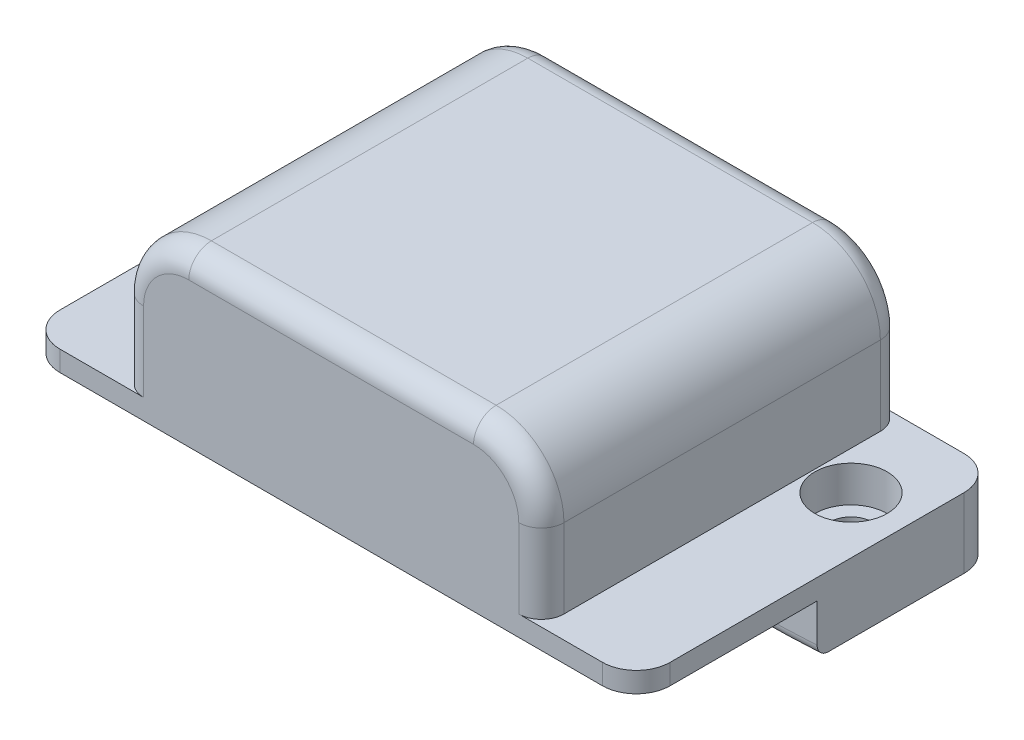
SolidWorks part; units mm, degrees
ref_plane "前视基准面" through (0, 0, 0) normal (0, 0, 1) x (1, 0, 0)
ref_plane "上视基准面" through (0, 0, 0) normal (0, 1, 0) x (1, 0, 0)
ref_plane "右视基准面" through (0, 0, 0) normal (1, 0, 0) x (0, 0, -1)
other "Configuration Table"
sketch "草图1" plane through (0, 0, 0) normal (0, 0, 1) x (1, 0, 0)
  line L0 (0, 65.0084) -> (0, -40.235) construction
  line L1 (-11, -3.0444) -> (-11, 5.3912) construction
  line L3 (55, 0) -> (-55, 0) construction
  line L8 (-13.5, 0) -> (-13.5, 3.5)
  line L9 (-13.5, 3.5) -> (-9.3, 3.5)
  line L10 (-9.3, 3.5) -> (-9.3, 10)
  line L11 (-9.3, 10) -> (9.3, 10)
  line L12 (9.3, 10) -> (9.3, 3.5)
  line L13 (9.3, 3.5) -> (13.5, 3.5)
  line L14 (13.5, 3.5) -> (13.5, 0)
  line L15 (-11, -3.0444) -> (11, -3.0444) construction
  line L16 (11, -3.0444) -> (11, 5.3912) construction
  line L17 (-13.5, 0) -> (13.5, 0)
  dimension "D1" = 10
  dimension "D2" = 27
  dimension "D3" = 18.6
  dimension "D4" = 3.5
  dimension "D5" = 22
extrude "凸台-拉伸1" add sketch "草图1" along normal mid plane 8
sketch "草图2" plane through (0, 0, 0) normal (0, -1, 0) x (1, 0, 0)
  line L0 (-15.998, 0) -> (16.2146, 0) construction
  line L2 (0, 10.6142) -> (0, -10.7139) construction
  circle A0 centre (-11, 0) radius 0.95
  circle A1 centre (11, 0) radius 0.95
  dimension "D2" = 1.9
  dimension "D1" = 22
extrude "切除-拉伸1" cut sketch "草图2" against normal up to next
sketch "草图3" plane through (0, 3.5, 0) normal (0, 1, 0) x (1, 0, 0)
  circle A0 centre (-11, 0) radius 1.5
  dimension "D1" = 3
sketch "草图5" plane through (0, 0, 0) normal (0, -1, 0) x (-1, 0, 0)
  line L0 (13.5, -4) -> (-13.5, -4) construction
  line L1 (7.8, -4) -> (-7.8, -4)
  line L2 (7.8, -4) -> (7.8, 2)
  line L3 (7.8, 2) -> (-7.8, 2)
  line L4 (-7.8, -4) -> (-7.8, 2)
  line L5 (0, -7.5091) -> (0, 7.4286) construction
  line L7 (9.3, -4) -> (9.3, 4) construction
  line L8 (13.5, 4) -> (-13.5, 4) construction
  dimension "D1" = 1.5
  dimension "D2" = 2
extrude "切除-拉伸2" cut sketch "草图5" against normal offset from surface (8.5 mm away) 1.5 up to face at (0, 10, 0)
sketch "草图8" plane through (0, 0, -4) normal (0, 0, -1) x (-1, 0, 0)
  line L0 (-18.4937, 0.9601) -> (-18.4937, -4.0399)
  line L1 (-18.4937, -4.0399) -> (18.4937, -4.0399)
  line L2 (18.4937, 0.9601) -> (18.4937, -4.0399)
  arc A0 (-18.4937, 0.9601) -> (-3.9261, 0.742) centre (-10.4695, 50.312) ccw construction
  arc A1 (3.9261, 0.742) -> (-3.9261, 0.742) centre (0, -29) ccw construction
  arc A2 (3.9261, 0.742) -> (18.4937, 0.9601) centre (10.4695, 50.312) ccw construction
  arc A3 (-18.4937, 0.9601) -> (-3.9261, 0.742) centre (-10.4695, 50.312) ccw
  arc A4 (3.9261, 0.742) -> (-3.9261, 0.742) centre (0, -29) ccw
  arc A5 (3.9261, 0.742) -> (18.4937, 0.9601) centre (10.4695, 50.312) ccw
  dimension "D1" = 5
extrude "切除-拉伸4" cut sketch "草图8" against normal through all
sketch "草图11" plane through (0, 0, 4) normal (0, 0, 1) x (1, 0, 0)
  line L0 (13.5, 2.6) -> (7.8, 2.6)
  line L1 (-7.8, 2.6) -> (-13.5, 2.6)
  line L7 (7.8, 8.5) -> (7.8, 0.3833)
  line L15 (-9.3, 10) -> (-9.3, 3.5)
  line L16 (-9.3, 3.5) -> (-13.5, 3.5)
  line L17 (-13.5, 3.5) -> (-13.5, 0.4039)
  line L18 (-7.8, 0.3833) -> (-7.8, 8.5)
  line L25 (-9.3, 10) -> (-9.3, 3.5)
  line L26 (-9.3, 3.5) -> (-13.5, 3.5)
  line L27 (-13.5, 3.5) -> (-13.5, 2.6)
  line L28 (-7.8, 2.6) -> (-7.8, 8.5)
  line L30 (7.8, 8.5) -> (7.8, 2.6)
  line L31 (13.5, 0.4039) -> (13.5, 3.5)
  line L32 (13.5, 2.6) -> (13.5, 3.5)
  line L33 (13.5, 3.5) -> (9.3, 3.5)
  line L34 (13.5, 3.5) -> (9.3, 3.5)
  line L35 (9.3, 3.5) -> (9.3, 10)
  line L36 (9.3, 3.5) -> (9.3, 10)
  line L37 (9.3, 10) -> (-9.3, 10)
  line L38 (9.3, 10) -> (-9.3, 10)
  line L39 (-7.8, 8.5) -> (7.8, 8.5)
  line L40 (-7.8, 8.5) -> (7.8, 8.5)
  arc A2 (7.8, 0.3833) -> (13.5, 0.4039) centre (10.4695, 50.312) ccw
  arc A3 (-13.5, 0.4039) -> (-7.8, 0.3833) centre (-10.4695, 50.312) ccw
  dimension "D2" = 0.9
  dimension "D1" = 0
extrude "凸台-拉伸2" add sketch "草图11" along normal blind 8
sketch "草图12" plane through (0, 8.5, 0) normal (0, -1, 0) x (1, 0, 0)
  line L0 (7.8, -2) -> (7.8, 12) construction
  line L1 (-7.8, 12) -> (7.8, 12)
  line L2 (-7.8, 12) -> (-7.8, 9)
  line L3 (-7.8, 9) -> (7.8, 9)
  line L4 (7.8, 12) -> (7.8, 9)
  dimension "D1" = 3
extrude "凸台-拉伸3" add sketch "草图12" along normal up to surface (5.9 mm away) up to face at (-10.65, 2.6, 8)
sketch "草图13" plane through (0, 3.5, 0) normal (0, 1, 0) x (1, 0, 0)
  circle A0 centre (-11, 0) radius 1.6
  circle A1 centre (11, 0) radius 1.6
  point P0 (-11, 0)
  point P1 (11, 0)
  dimension "D1" = 3.2
extrude "切除-拉伸5" cut sketch "草图13" against normal blind 1.6
fillet "圆角1" radius 3 2 edges at (9.3, 10, 4) (-9.3, 10, 4)
fillet "圆角2" radius 1 2 edges at (-7.8, 8.5, 3.5) (7.8, 8.5, 3.5)
fillet "圆角3" radius 1.5 4 edges at (13.5, 3.05, 12) (-13.5, 3.05, 12) (-13.5, 1.9519, -4) (13.5, 1.9519, -4)
fillet "圆角4" radius 1 10 edges at (-9.3, 5.25, -4) (-8.4213, 9.1213, -4) (0, 10, -4) (8.4213, 9.1213, -4) (-9.3, 5.25, 12) (-8.4213, 9.1213, 12) (0, 10, 12) (8.4213, 9.1213, 12) (9.3, 5.25, -4) (9.3, 5.25, 12)
fillet "圆角5" radius 0.5 2 edges at (-10.6503, 0.3123, 4) (10.6503, 0.3123, 4)
fillet "圆角6" radius 0.5 10 edges at (-7.8, 3.9416, -2) (-7.5071, 8.2071, -2) (0, 8.5, -2) (7.5071, 8.2071, -2) (-7.8, 5.05, 9) (-7.5071, 8.2071, 9) (0, 8.5, 9) (7.5071, 8.2071, 9) (7.8, 3.9416, -2) (7.8, 5.05, 9)
